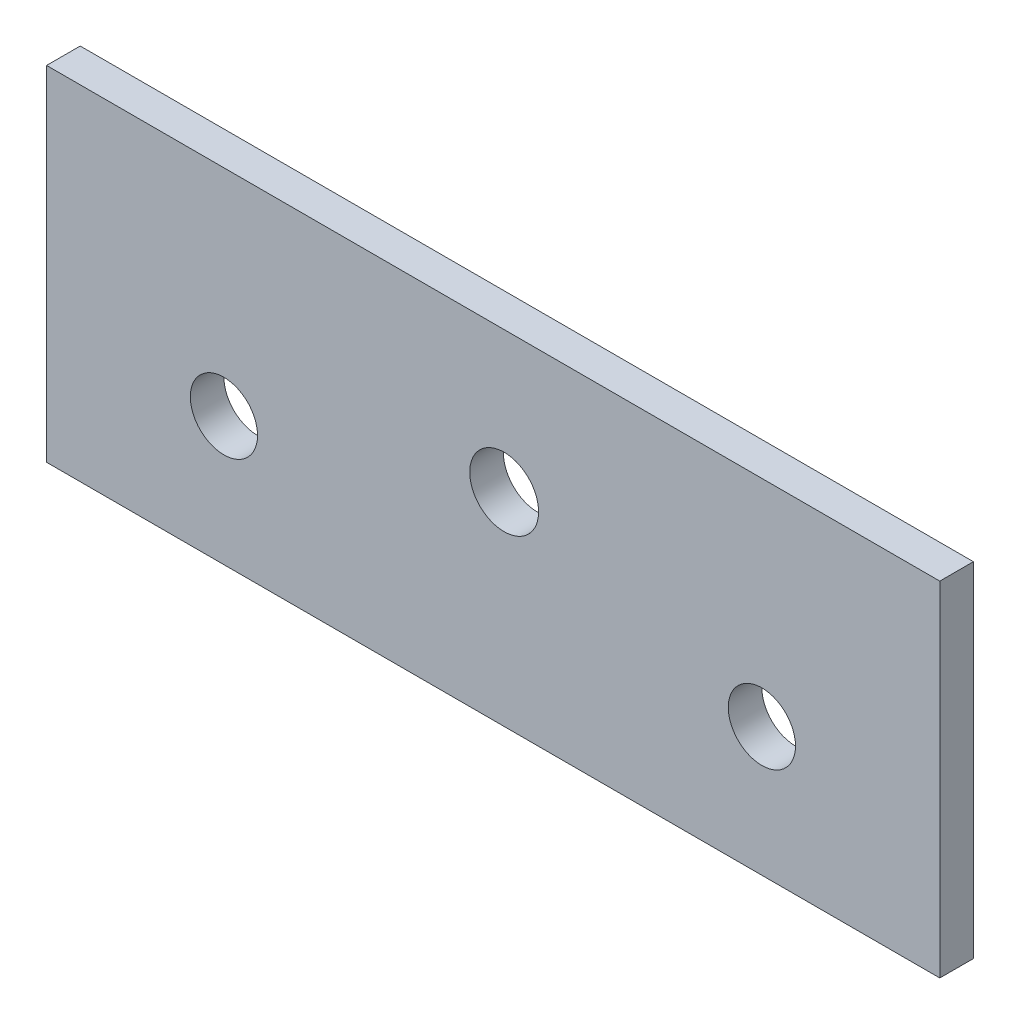
SolidWorks part; units mm, degrees
ref_plane "Front Plane" through (0, 0, 0) normal (0, 0, 1) x (1, 0, 0)
ref_plane "Top Plane" through (0, 0, 0) normal (0, 1, 0) x (1, 0, 0)
ref_plane "Right Plane" through (0, 0, 0) normal (1, 0, 0) x (0, 0, -1)
sketch "Sketch1" plane through (0, 0, 0) normal (0, 0, 1) x (1, 0, 0)
  line L1 (8.6551, -156.5891) -> (92.9991, -156.5891)
  line L2 (8.6551, -156.5891) -> (8.6551, -189.0473)
  line L3 (8.6551, -189.0473) -> (92.9991, -189.0473)
  line L4 (92.9991, -156.5891) -> (92.9991, -189.0473)
  circle A0 centre (25.4, -176.8929) radius 3.175
  circle A1 centre (76.2, -176.8929) radius 3.175
  circle A2 centre (51.862, -169.8682) radius 3.2512
  circle A3 centre (51.862, -169.8682) radius 3.175 construction
  dimension "D1" = 6.5024
  dimension "D2" = 6.35
  dimension "D3" = 6.35
extrude "Boss-Extrude1" add sketch "Sketch1" along normal blind 3.175
